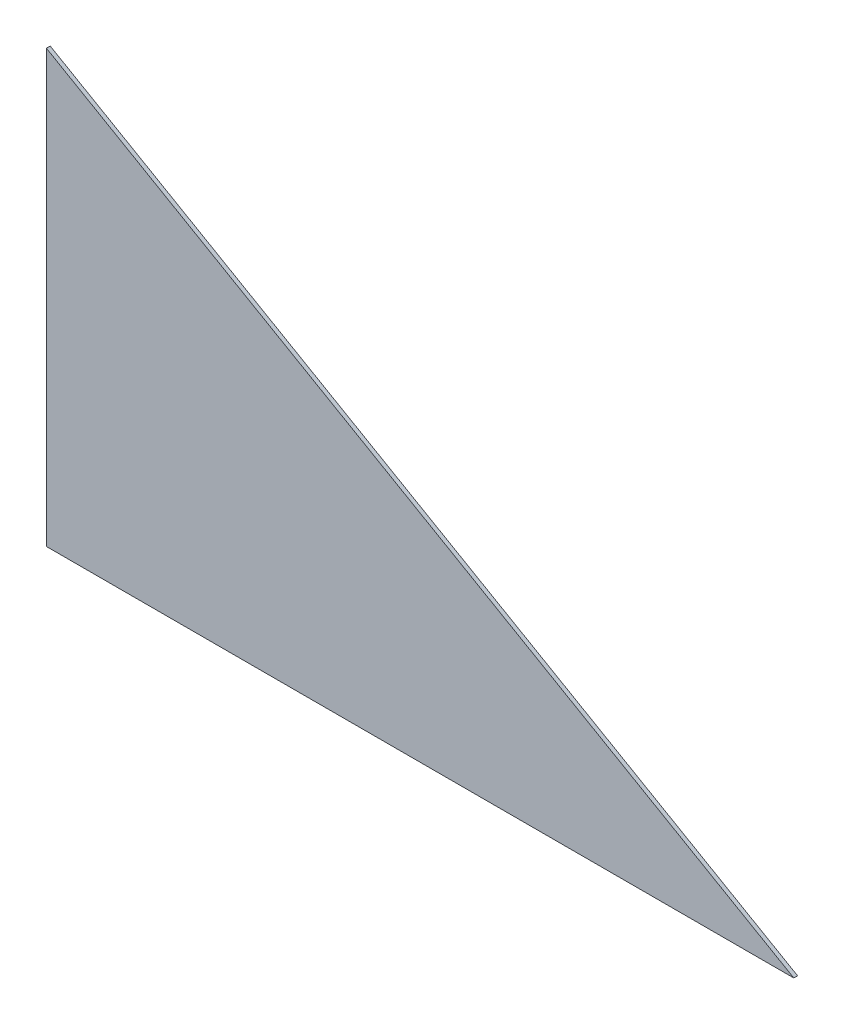
SolidWorks part; units mm, degrees
ref_plane "Front Plane" through (0, 0, 0) normal (0, 0, 1) x (1, 0, 0)
ref_plane "Top Plane" through (0, 0, 0) normal (0, 1, 0) x (1, 0, 0)
ref_plane "Right Plane" through (0, 0, 0) normal (1, 0, 0) x (0, 0, -1)
sketch "Sketch1" plane through (0, 0, 0) normal (0, 0, 1) x (1, 0, 0)
  line L0 (0, 0) -> (0, 144.3376)
  line L1 (0, 144.3376) -> (250, 0)
  line L2 (250, 0) -> (0, 0)
  dimension "D1" = 250
  dimension "D2" = 60
extrude "Boss-Extrude1" add sketch "Sketch1" along normal blind 1.27
sketch "Sketch2" plane through (0, 0, 1.27) normal (0, 0, 1) x (1, 0, 0)
  line L0 (84.6608, 194.507) -> (333.9941, 194.507) construction
sketch "Sketch3" plane through (0, 0, 0) normal (0, 0, -1) x (-1, 0, 0)
  line L0 (-30.2728, 191.374) -> (219.0605, 191.374) construction
